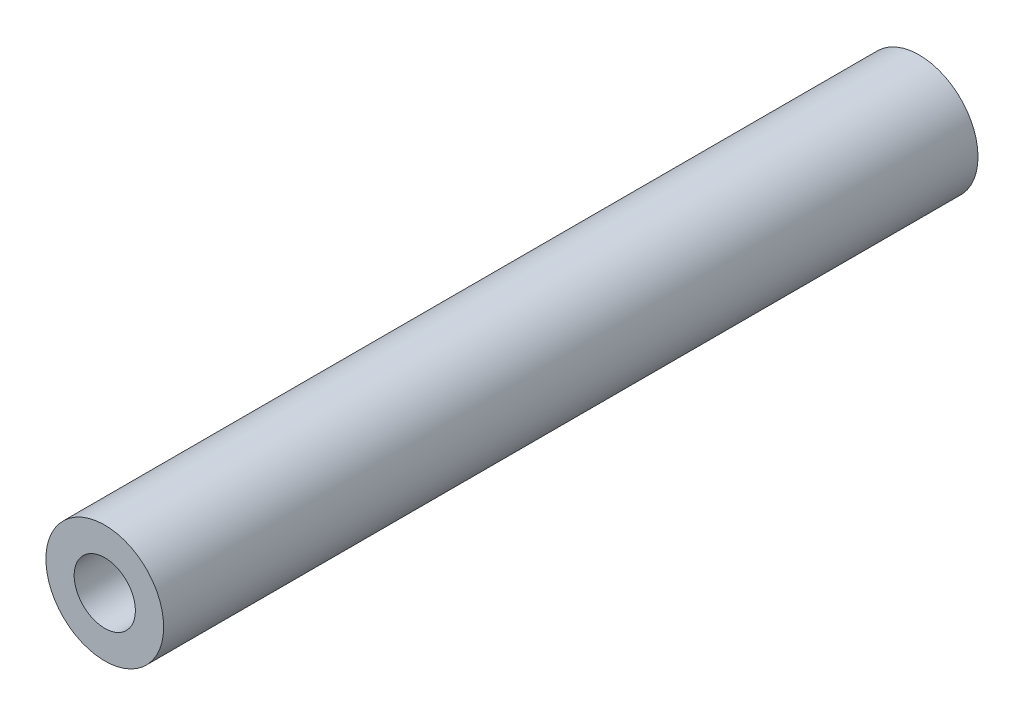
SolidWorks part; units mm, degrees
material "6061-T6 (SS)"
ref_plane "Front Plane" through (0, 0, 0) normal (0, 0, 1) x (1, 0, 0)
ref_plane "Top Plane" through (0, 0, 0) normal (0, 1, 0) x (1, 0, 0)
ref_plane "Right Plane" through (0, 0, 0) normal (1, 0, 0) x (0, 0, -1)
sketch "Sketch1" plane through (0, 0, 0) normal (0, 0, 1) x (1, 0, 0)
  circle A0 centre (0, 0) radius 1.5875
  circle A1 centre (0, 0) radius 0.8255
  dimension "D1" = 1.651
  dimension "D2" = 3.175
extrude "Extrude1" add sketch "Sketch1" along normal blind 21.9577
